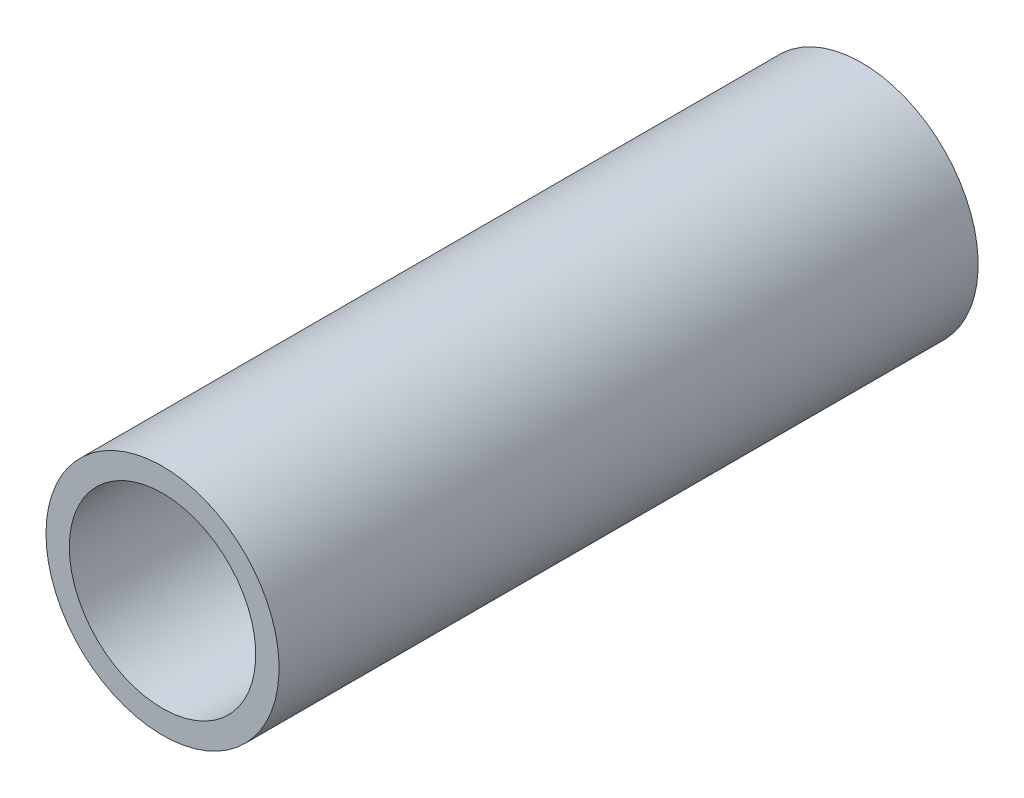
SolidWorks part; units mm, degrees
ref_plane "Front Plane" through (0, 0, 0) normal (0, 0, 1) x (1, 0, 0)
ref_plane "Top Plane" through (0, 0, 0) normal (0, 1, 0) x (1, 0, 0)
ref_plane "Right Plane" through (0, 0, 0) normal (1, 0, 0) x (0, 0, -1)
sketch "Sketch1" plane through (0, 0, 0) normal (0, 0, 1) x (1, 0, 0)
  circle A0 centre (0, 0) radius 7.5
  circle A1 centre (0, 0) radius 6
  dimension "D1" = 15
  dimension "D2" = 12
extrude "Boss-Extrude1" add sketch "Sketch1" along normal blind 45
